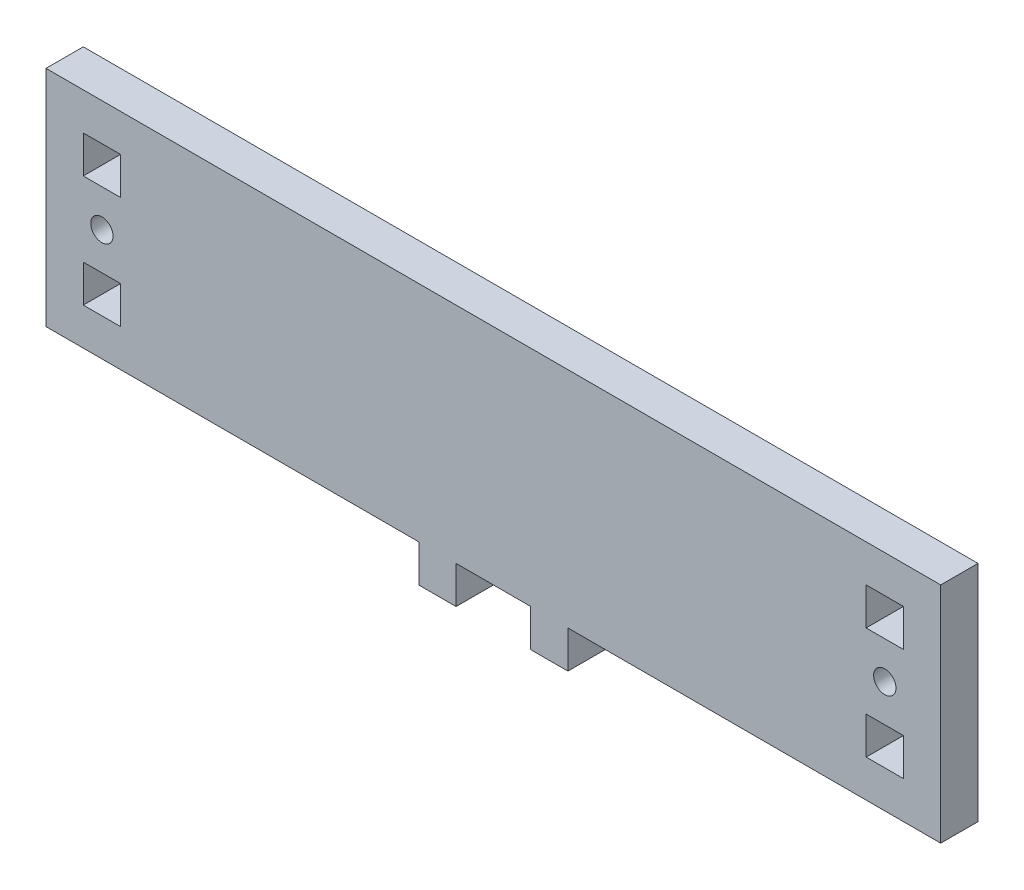
SolidWorks part; units mm, degrees
ref_plane "Front Plane" through (0, 0, 0) normal (0, 0, 1) x (1, 0, 0)
ref_plane "Top Plane" through (0, 0, 0) normal (0, 1, 0) x (1, 0, 0)
ref_plane "Right Plane" through (0, 0, 0) normal (1, 0, 0) x (0, 0, -1)
sketch "Sketch1" plane through (0, 0, 0) normal (0, 0, 1) x (1, 0, 0)
  line L0 (0, 0) -> (0, 5.0154)
  line L1 (0, 5.0154) -> (-10, 5.0154)
  line L2 (-10, 5.0154) -> (-10, 0)
  line L3 (-10, 0) -> (-15, 0)
  line L4 (-15, 0) -> (-15, 5.0154)
  line L5 (-15, 5.0154) -> (-65, 5.0154)
  line L6 (-65, 5.0154) -> (-65, 35.0154)
  line L7 (-65, 35.0154) -> (55, 35.0154)
  line L8 (55, 35.0154) -> (55, 5.0154)
  line L9 (55, 5.0154) -> (5, 5.0154)
  line L10 (5, 5.0154) -> (5, 0)
  line L11 (5, 0) -> (0, 0)
  line L12 (-5, 41.9705) -> (-5, -5.7911) construction
  point P15 (-5, 35.0154)
  line B0 (-57.5, 15.0154) -> (-57.5, 25.0154) construction
  line B1 (-60, 15.0154) -> (-60, 10.0154)
  line B2 (-60, 15.0154) -> (-55, 15.0154)
  line B3 (-55, 15.0154) -> (-55, 10.0154)
  line B4 (-60, 10.0154) -> (-55, 10.0154)
  line B5 (-60, 25.0154) -> (-60, 30.0154)
  line B6 (-60, 25.0154) -> (-55, 25.0154)
  line B7 (-55, 25.0154) -> (-55, 30.0154)
  line B8 (-60, 30.0154) -> (-55, 30.0154)
  line B9 (-57.5, 20.0154) -> (-63.7802, 20.0154) construction
  circle B10 centre (-57.5, 20.0154) radius 1.5
  line B11 (47.5, 15.0154) -> (47.5, 25.0154) construction
  line B12 (45, 15.0154) -> (45, 10.0154)
  line B13 (45, 15.0154) -> (50, 15.0154)
  line B14 (50, 15.0154) -> (50, 10.0154)
  line B15 (45, 10.0154) -> (50, 10.0154)
  line B16 (45, 25.0154) -> (45, 30.0154)
  line B17 (45, 25.0154) -> (50, 25.0154)
  line B18 (50, 25.0154) -> (50, 30.0154)
  line B19 (45, 30.0154) -> (50, 30.0154)
  line B20 (47.5, 20.0154) -> (41.2198, 20.0154) construction
  circle B21 centre (47.5, 20.0154) radius 1.5
sketch_block_instance "Trou M3 plots 5mm-52"
sketch_block "Trou M3 plots 5mm" parameters "D2"=3, "D1"=5, "D3"=5, "D4"=8
sketch_block_instance "Trou M3 plots 5mm-53" parameters "D1"=6.2961, "D2"=5.3289, "D3"=9.4737, "D4"=31.7383, "D5"=14.2161, "D6"=5
extrude "Boss-Extrude1" add sketch "Sketch1" along normal blind 5
